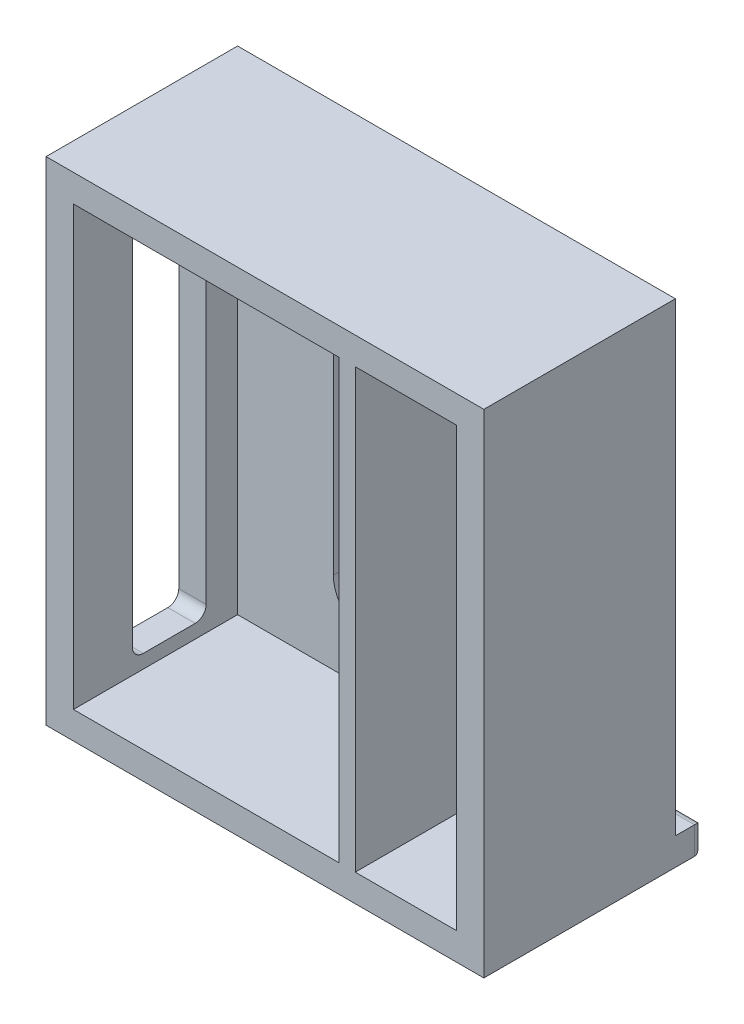
SolidWorks part; units mm, degrees
ref_plane "前视基准面" through (0, 0, 0) normal (0, 0, 1) x (1, 0, 0)
ref_plane "上视基准面" through (0, 0, 0) normal (0, 1, 0) x (1, 0, 0)
ref_plane "右视基准面" through (0, 0, 0) normal (1, 0, 0) x (0, 0, -1)
sketch "草图1" plane through (0, 0, 0) normal (0, 1, 0) x (1, 0, 0)
  line L1 (-80, 35) -> (80, 35)
  line L2 (-80, 35) -> (-80, -35)
  line L3 (-80, -35) -> (80, -35)
  line L4 (80, 35) -> (80, -35)
  line L5 (-80, 35) -> (80, -35) construction
  line L6 (-80, -35) -> (80, 35) construction
  point P0 (0, 0)
  dimension "D1" = 70
  dimension "D2" = 160
extrude "凸台-拉伸1" add sketch "草图1" along normal blind 180
shell "抽壳1" thickness 10
sketch "草图2" plane through (0, 0, 0) normal (0, -1, 0) x (1, 0, 0)
  line L0 (30, 35) -> (30, -35)
  line L1 (-80, 35) -> (80, 35) construction
  line L2 (80, -35) -> (-80, -35) construction
  line L3 (80, 35) -> (80, -35) construction
  line L4 (27, 35) -> (27, -35)
  line L5 (33, 35) -> (33, -35)
  line L6 (33, -35) -> (27, -35)
  line L7 (27, 35) -> (33, 35)
  line M3 (80, 35) -> (-80, 35)
  line M5 (-80, -35) -> (80, -35)
  dimension "D1" = 50
  dimension "D2" = 3
  dimension "D3" = 3
extrude "凸台-拉伸2" add sketch "草图2" against normal up to surface (170 mm away) contours L5 L0 M3 M5 | L4 L0 M3 M5 up to face at (0, 170, 5)
sketch "草图3" plane through (0, 0, -25) normal (0, 0, 1) x (1, 0, 0)
  line L0 (-21.5, 140) -> (-21.5, 40) construction
  line L1 (-8, 140) -> (-8, 40)
  line L2 (-35, 140) -> (-35, 40)
  line L3 (-70, 170) -> (27, 170) construction
  line L4 (-70, 170) -> (-70, 10) construction
  arc A0 (-8, 140) -> (-35, 140) centre (-21.5, 140) ccw
  arc A1 (-35, 40) -> (-8, 40) centre (-21.5, 40) ccw
  point P2 (-21.5, 90)
  point P9 (-21.5, 170)
  point P12 (-70, 90)
  dimension "D1" = 27
  dimension "D2" = 100
extrude "切除-拉伸1" cut sketch "草图3" against normal blind 170
sketch "草图4" plane through (0, 0, -25) normal (0, 0, 1) x (1, 0, 0)
  line L0 (51.5, 137.5) -> (51.5, 42.5) construction
  line L1 (59, 137.5) -> (59, 42.5)
  line L2 (44, 137.5) -> (44, 42.5)
  line L3 (70, 170) -> (70, 10) construction
  line L4 (70, 10) -> (33, 10) construction
  arc A0 (59, 137.5) -> (44, 137.5) centre (51.5, 137.5) ccw
  arc A1 (44, 42.5) -> (59, 42.5) centre (51.5, 42.5) ccw
  point P2 (51.5, 90)
  point P9 (70, 90)
  point P12 (51.5, 10)
  dimension "D1" = 15
  dimension "D2" = 95
extrude "切除-拉伸2" cut sketch "草图4" against normal blind 170
sketch "草图5" plane through (-80, 0, 0) normal (-1, 0, 0) x (0, 0, 1)
  line L1 (-9.5, 165) -> (9.5, 165)
  line L2 (-13.5, 161) -> (-13.5, 19)
  line L3 (-9.5, 15) -> (9.5, 15)
  line L4 (13.5, 161) -> (13.5, 19)
  line L5 (-13.5, 165) -> (13.5, 15) construction
  line L6 (-13.5, 15) -> (13.5, 165) construction
  arc A0 (9.5, 165) -> (13.5, 161) centre (9.5, 161) cw
  arc A1 (-13.5, 19) -> (-9.5, 15) centre (-9.5, 19) ccw
  arc A2 (-9.5, 165) -> (-13.5, 161) centre (-9.5, 161) ccw
  arc A3 (9.5, 15) -> (13.5, 19) centre (9.5, 19) ccw
  point P0 (0, 90)
  point P5 (0, 0)
  dimension "D3" = 4
  dimension "D1" = 150
  dimension "D2" = 27
extrude "切除-拉伸3" cut sketch "草图5" against normal up to next
sketch "草图6" plane through (0, 0, -35) normal (0, 0, -1) x (-1, 0, 0)
  line L0 (80, 180) -> (80, 0) construction
  line L1 (-80, 0) -> (80, 0)
  line L2 (-80, 0) -> (-80, 10)
  line L3 (-80, 10) -> (80, 10)
  line L4 (80, 0) -> (80, 10)
  dimension "D1" = 10
extrude "凸台-拉伸3" add sketch "草图6" along normal blind 10
fillet "圆角1" radius 3 4 edges at (0, 10, -45) (-80, 5, -45) (0, 0, -45) (80, 5, -45)
